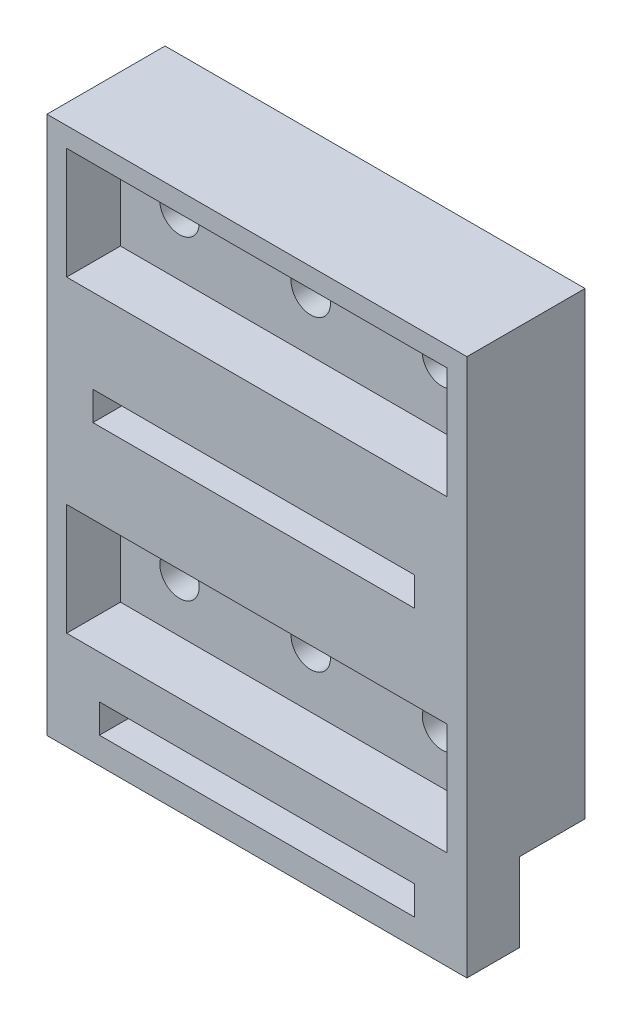
SolidWorks part; units mm, degrees
material "ABS"
ref_plane "Front Plane" through (0, 0, 0) normal (0, 0, 1) x (1, 0, 0)
ref_plane "Top Plane" through (0, 0, 0) normal (0, 1, 0) x (1, 0, 0)
ref_plane "Right Plane" through (0, 0, 0) normal (1, 0, 0) x (0, 0, -1)
sketch "Sketch4" plane through (0, 0, 0) normal (0, 0, 1) x (1, 0, 0)
  line L0 (-16, 17.5) -> (16, -17.5) construction
  line L1 (-16, 17.5) -> (16, 17.5)
  line L2 (-16, 17.5) -> (-16, -17.5)
  line L3 (-16, -17.5) -> (16, -17.5)
  line L4 (16, 17.5) -> (16, -17.5)
  line L5 (16, 17.5) -> (-16, -17.5) construction
  point P4 (0, 0)
  dimension "D1" = 32
  dimension "D2" = 35
extrude "Boss-Extrude1" add sketch "Sketch4" along normal blind 9
shell "Shell1" thickness 1.5
sketch "Sketch5" plane through (0, 0, 4.9) normal (0, 0, 1) x (1, 0, 0)
  line L0 (-14.5, 15) -> (-14.5, -15) construction
  line L1 (-14.5, -15) -> (14.5, -15) construction
  line L2 (14.5, -15) -> (14.5, 15) construction
  line L3 (14.5, 15) -> (-14.5, 15) construction
  line L4 (-14.5, 15) -> (14.5, -15) construction
  line L5 (0, 18.6176) -> (0, -20.2425) construction
  line L6 (12.1043, 0) -> (-43.3409, 0) construction
  circle A0 centre (-10, -12) radius 1.5
  circle A1 centre (10, -12) radius 1.5
  circle A2 centre (0, 11.7) radius 1.5
  circle A3 centre (0, -11.7) radius 1.5
  circle A4 centre (-10, 12) radius 1.5
  circle A5 centre (10, 12) radius 1.5
  point P4 (0, 0)
  dimension "D7" = 3
  dimension "D1" = 29
  dimension "D2" = 30
  dimension "D3" = 20
  dimension "D4" = 3
  dimension "D5" = 10
  dimension "D6" = 23.7
extrude "Cut-Extrude2" cut sketch "Sketch5" against normal blind 9
sketch "Sketch12" plane through (0, 0, 9) normal (0, 0, 1) x (1, 0, 0)
  line L0 (14.5, 0) -> (-14.5, 0)
  line L1 (14.5, -16) -> (14.5, 16) construction
  line L2 (-14.5, 16) -> (-14.5, -16) construction
rib "Rib6" sketch "Sketch12" sketch "Sketch12" thickness 15 parameters "D1"=15
sketch "Sketch13" plane through (0, 0, 0) normal (0, 0, -1) x (-1, 0, 0)
  line L0 (16, -17.5) -> (-16, -17.5) construction
  line L1 (14, -5) -> (-14, -5)
  line L2 (14, -5) -> (14, 5)
  line L3 (14, 5) -> (-14, 5)
  line L4 (-14, -5) -> (-14, 5)
  line L5 (-16, 17.5) -> (16, 17.5) construction
  line L6 (16, 17.5) -> (16, -17.5) construction
  line L7 (-16, -17.5) -> (-16, 17.5) construction
  dimension "D1" = 12.5
  dimension "D2" = 12.5
  dimension "D3" = 2
  dimension "D4" = 2
extrude "Cut-Extrude3" cut sketch "Sketch13" against normal blind 5
sketch "Sketch15" plane through (0, 0, 5) normal (0, 0, -1) x (-1, 0, 0)
  line L1 (12.5, 1.1) -> (-12, 1.1)
  line L2 (12.5, 1.1) -> (12.5, -1.1)
  line L3 (12.5, -1.1) -> (-12, -1.1)
  line L4 (-12, 1.1) -> (-12, -1.1)
  line L6 (14.5, -5) -> (14.5, 5) construction
  line L7 (-14, 5) -> (-14, -5) construction
  dimension "D1" = 2.2
  dimension "D2" = 1.1
  dimension "D3" = 2
  dimension "D4" = 2
extrude "Cut-Extrude4" cut sketch "Sketch15" against normal blind 10
sketch "Sketch16" plane through (0, -17.5, 0) normal (0, -1, 0) x (1, 0, 0)
  line L0 (-16, 9) -> (-16, 0) construction
  line L1 (16, 9) -> (-16, 9)
  line L2 (16, 9) -> (16, 5)
  line L3 (16, 5) -> (-16, 5)
  line L4 (-16, 9) -> (-16, 5)
  dimension "D1" = 4
extrude "Boss-Extrude2" add sketch "Sketch16" along normal blind 6
sketch "Sketch17" plane through (0, 0, 9) normal (0, 0, 1) x (1, 0, 0)
  line L0 (-12.5, -1.1) -> (12, -1.1) construction
  line L1 (12, -21.48) -> (-12, -21.48)
  line L2 (12, -21.48) -> (12, -19.28)
  line L3 (12, -19.28) -> (-12, -19.28)
  line L4 (-12, -21.48) -> (-12, -19.28)
  line L6 (16, -23.5) -> (16, 17.5) construction
  line L7 (-16, 17.5) -> (-16, -23.5) construction
  dimension "D1" = 18.18
  dimension "D2" = 4
  dimension "D3" = 2.2
  dimension "44" = 4
extrude "Cut-Extrude5" cut sketch "Sketch17" against normal blind 10
